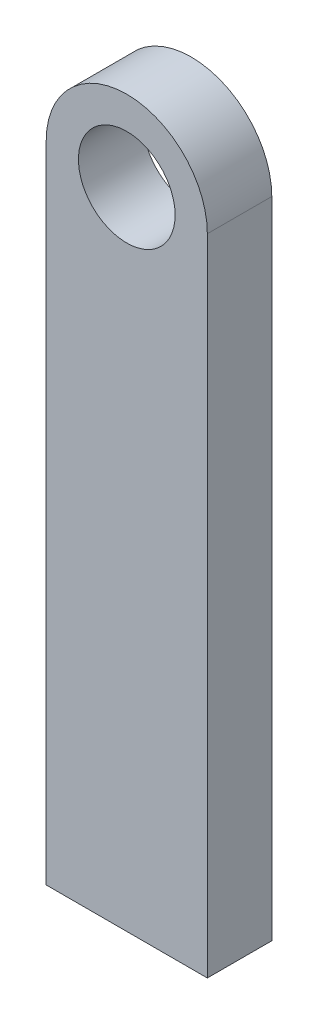
SolidWorks part; units mm, degrees
ref_plane "Front Plane" through (0, 0, 0) normal (0, 0, 1) x (1, 0, 0)
ref_plane "Top Plane" through (0, 0, 0) normal (0, 1, 0) x (1, 0, 0)
ref_plane "Right Plane" through (0, 0, 0) normal (1, 0, 0) x (0, 0, -1)
sketch "Sketch1" plane through (0, 0, 0) normal (0, 0, 1) x (1, 0, 0)
  line L0 (-2.5, 0) -> (-2.5, -20)
  line L1 (-2.5, -20) -> (2.5, -20)
  line L2 (2.5, -20) -> (2.5, 0)
  circle A0 centre (0, 0) radius 1.5
  arc A1 (2.5, 0) -> (-2.5, 0) centre (0, 0) ccw
  point P8 (2.5, 0)
  point P9 (-2.6966, 3.5458)
  point P10 (0, 0)
  dimension "D1" = 3
  dimension "D3" = 20
  dimension "D4" = 5
extrude "Boss-Extrude1" add sketch "Sketch1" along normal blind 2
